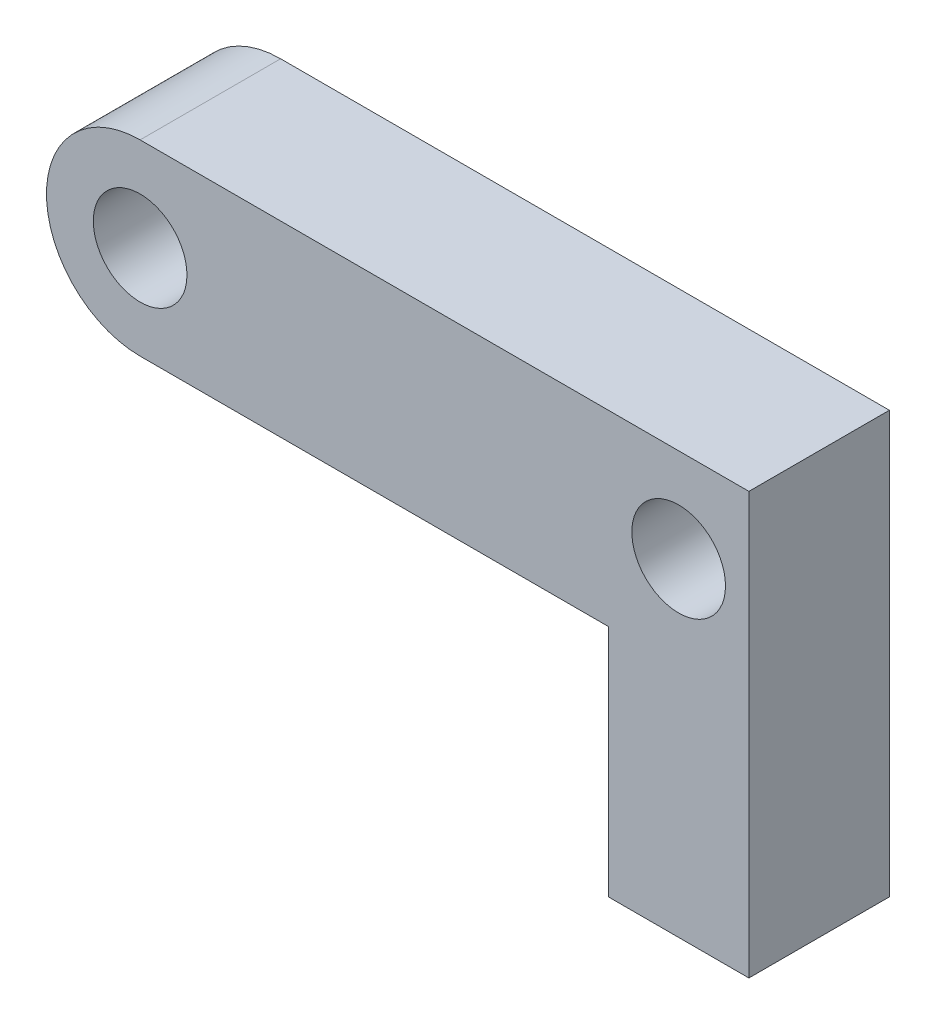
SolidWorks part; units mm, degrees
ref_plane "Front Plane" through (0, 0, 0) normal (1, 0, 0) x (0, 1, 0)
ref_plane "Top Plane" through (0, 0, 0) normal (0, 0, 1) x (0, 1, 0)
ref_plane "Right Plane" through (0, 0, 0) normal (0, 1, 0) x (-1, 0, 0)
sketch "Sketch1" plane through (0, 0, 0) normal (0, 0, 1) x (0, 1, 0)
  line L0 (-20, 0) -> (-20, -100)
  line L1 (-20, -100) -> (-70, -100)
  line L2 (-70, -100) -> (-70, -130)
  line L3 (20, 0) -> (20, -130)
  line L4 (20, -130) -> (-70, -130)
  arc A0 (20, 0) -> (-20, 0) centre (0, 0) ccw
  dimension "D1" = 40
  dimension "D2" = 100
  dimension "D3" = 30
  dimension "D4" = 50
extrude "Boss-Extrude1" add sketch "Sketch1" along normal blind 30
sketch "Sketch2" plane through (0, -70, 0) normal (0, -1, 0) x (1, 0, 0)
  line L0 (115, 30) -> (115, 0) construction
  line L1 (100, 30) -> (130, 30) construction
  line L2 (100, 0) -> (130, 0) construction
  circle A0 centre (115, 15) radius 8
  dimension "D1" = 16
extrude "Cut-Extrude1" cut sketch "Sketch2" against normal blind 30
sketch "Sketch3" plane through (0, 0, 30) normal (0, 0, 1) x (1, 0, 0)
  line L0 (115, -70) -> (115, 20) construction
  line L1 (100, -70) -> (130, -70) construction
  line L2 (130, 20) -> (0, 20) construction
  line L3 (-20, 0) -> (130, 0) construction
  line L4 (130, -70) -> (130, 20) construction
  circle A0 centre (0, 0) radius 10
  arc A1 (0, 20) -> (0, -20) centre (0, 0) ccw construction
  circle A2 centre (115, 0) radius 10
  dimension "D1" = 20
  dimension "D2" = 20
extrude "Cut-Extrude2" cut sketch "Sketch3" against normal blind 30
